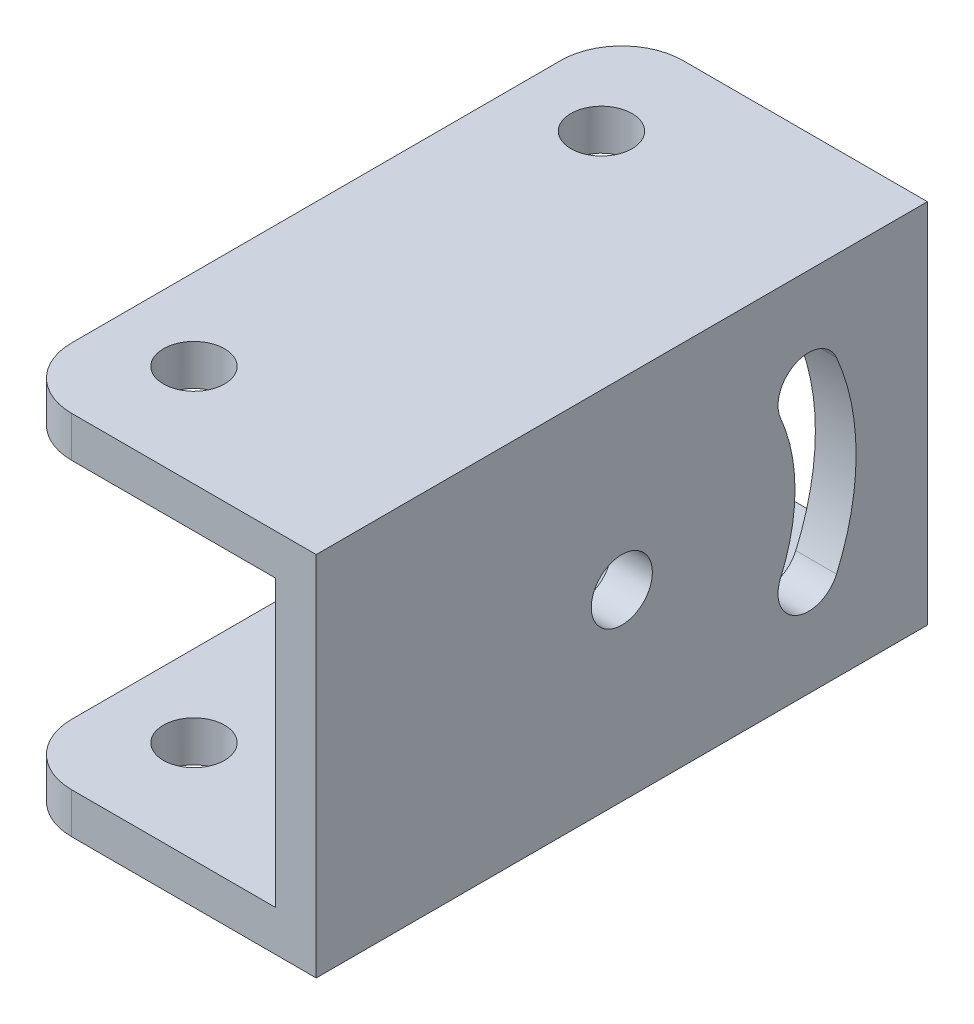
SolidWorks part; units mm, degrees
material "ABS"
ref_plane "Front Plane" through (0, 0, 0) normal (0, 0, 1) x (1, 0, 0)
ref_plane "Top Plane" through (0, 0, 0) normal (0, 1, 0) x (1, 0, 0)
ref_plane "Right Plane" through (0, 0, 0) normal (1, 0, 0) x (0, 0, -1)
sketch "Sketch1" plane through (0, 0, 0) normal (0, 0, 1) x (1, 0, 0)
  line L0 (0, 0) -> (15, 0)
  line L1 (15, 0) -> (15, 18)
  line L2 (15, 18) -> (0, 18)
  line L3 (0, 18) -> (0, 16)
  line L4 (0, 16) -> (13, 16)
  line L5 (13, 16) -> (13, 2)
  line L6 (13, 2) -> (0, 2)
  line L7 (0, 2) -> (0, 0)
  dimension "D1" = 18
  dimension "D2" = 15
  dimension "D3" = 13
  dimension "D4" = 2
  dimension "D5" = 2
extrude "Boss-Extrude1" add sketch "Sketch1" along normal blind 30
sketch "Sketch2" plane through (0, 18, 0) normal (0, 1, 0) x (1, 0, 0)
  line L0 (4, 3.7019) -> (4, -33.5199) construction
  line L1 (15, -30) -> (15, 0) construction
  line L2 (15, -30) -> (0, -30) construction
  line L3 (-5.1718, -5) -> (24.0958, -5) construction
  line L4 (-1.9198, -25) -> (25.8696, -25) construction
  circle A0 centre (4, -5) radius 1.5
  circle A1 centre (4, -25) radius 1.5
  point P8 (9.462, -5)
  point P11 (7.5, -30)
  point P12 (4, -5)
  point P13 (4, -25)
  dimension "D4" = 3
  dimension "D5" = 3
  dimension "D1" = 11
  dimension "D2" = 20
  dimension "D3" = 5
extrude "Cut-Extrude1" cut sketch "Sketch2" against normal through all
fillet "Fillet1" radius 3 4 edges at (0, 1, 30) (0, 1, 0) (0, 17, 0) (0, 17, 30)
sketch "Sketch3" plane through (15, 0, 0) normal (1, 0, 0) x (0, 0, -1)
  line L0 (-15, 22.1856) -> (-15, -5.6624) construction
  line L1 (0, 9) -> (-32.2995, 9) construction
  line L2 (0, 0) -> (0, 18) construction
  line L3 (-30, 0) -> (0, 0) construction
  line L4 (-30, 0) -> (-30, 18) construction
  circle A0 centre (-15, 9) radius 1.5
  arc A1 (-5.8348, 13) -> (-5.8348, 5) centre (-15, 9) cw construction
  arc A2 (-4.4601, 4.4) -> (-4.4601, 13.6) centre (-15, 9) ccw
  arc A3 (-7.2096, 5.6) -> (-7.2096, 12.4) centre (-15, 9) ccw
  arc A4 (-7.2096, 5.6) -> (-4.4601, 4.4) centre (-5.8348, 5) ccw
  arc A5 (-4.4601, 13.6) -> (-7.2096, 12.4) centre (-5.8348, 13) ccw
  point P12 (-15, 9)
  point P15 (-5, 9)
  dimension "D3" = 3
  dimension "D5" = 8
  dimension "D6" = 1.5
  dimension "D1" = 9
  dimension "D2" = 15
  dimension "D4" = 10
extrude "Cut-Extrude2" cut sketch "Sketch3" against normal blind 30
